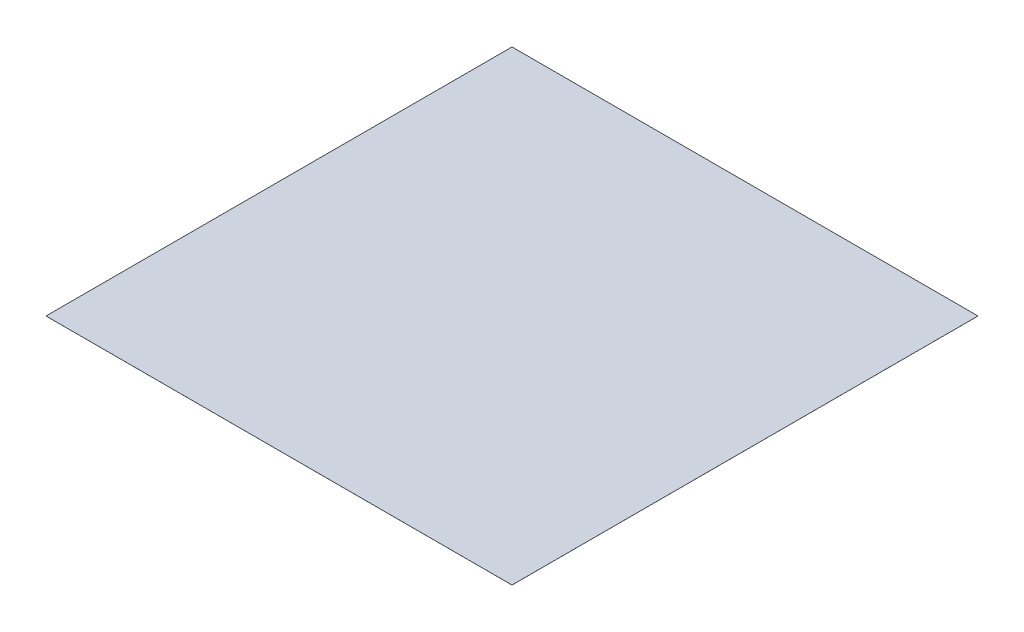
SolidWorks part; units mm, degrees
ref_plane "Front Plane" through (0, 0, 0) normal (0, 0, 1) x (1, 0, 0)
ref_plane "Top Plane" through (0, 0, 0) normal (0, 1, 0) x (1, 0, 0)
ref_plane "Right Plane" through (0, 0, 0) normal (1, 0, 0) x (0, 0, -1)
sketch "Sketch1" plane through (0, 0, 0) normal (0, 1, 0) x (1, 0, 0)
  line L1 (100, -100) -> (-100, -100)
  line L2 (100, -100) -> (100, 100)
  line L3 (100, 100) -> (-100, 100)
  line L4 (-100, -100) -> (-100, 100)
  line L5 (100, -100) -> (-100, 100) construction
  line L6 (100, 100) -> (-100, -100) construction
  point P0 (0, 0)
  dimension "D1" = 200
  dimension "D2" = 200
extrude "Boss-Extrude1" add sketch "Sketch1" along normal blind 0.01
